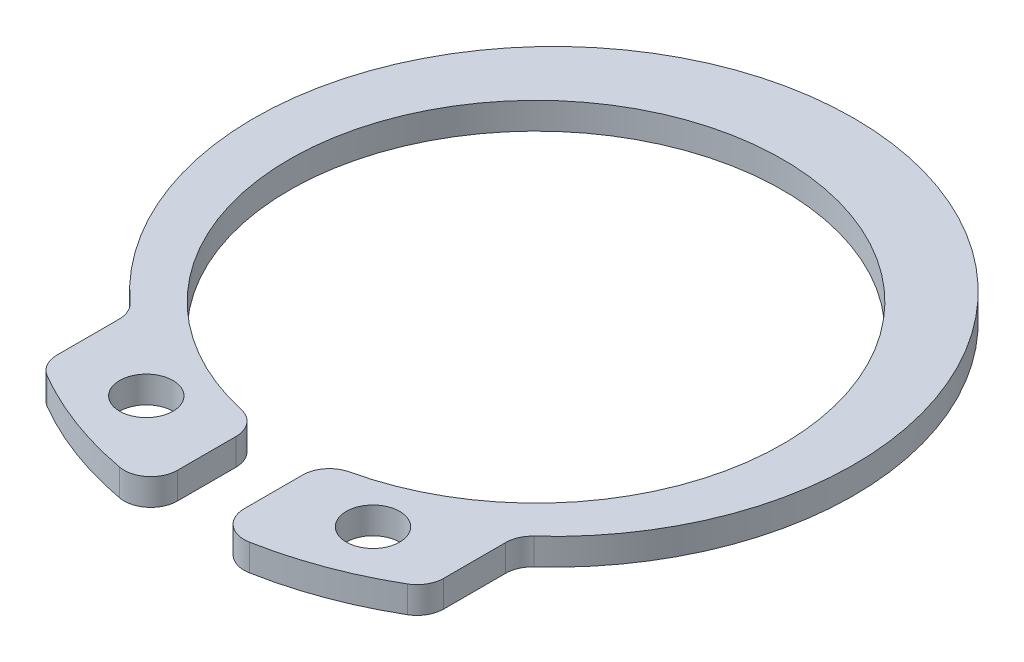
SolidWorks part; units mm, degrees
material "铸造合金钢"
ref_plane "Front" through (0, 0, 0) normal (0, 0, 1) x (1, 0, 0)
ref_plane "Top" through (0, 0, 0) normal (0, 1, 0) x (1, 0, 0)
ref_plane "Right" through (0, 0, 0) normal (1, 0, 0) x (0, 0, -1)
sketch "草图1" plane through (0, 0, 0) normal (0, 1, 0) x (1, 0, 0)
  line L0 (0, 6.1653) -> (0, -2.3077) construction
  line L1 (-1.25, -13.3416) -> (-1.25, -9.1652)
  line L2 (1.25, -13.3416) -> (1.25, -9.1652)
  line L3 (-4.25, -2.5592) -> (-4.25, -10.3623) construction
  line L4 (-7.25, -7.9323) -> (-7.25, -11.2693)
  line L5 (7.25, -7.9323) -> (7.25, -11.2693)
  line L6 (4.25, -2.5592) -> (4.25, -10.3623) construction
  line L7 (11.2, 0) -> (-11.2, 0) construction
  line L8 (0, 0) -> (-1.8108, -13.2771) construction
  arc A0 (1.25, -9.1652) -> (-1.25, -9.1652) centre (0, 0) ccw
  arc A1 (7.25, -7.9323) -> (-7.25, -7.9323) centre (0, 0.67) ccw
  arc A2 (-11.2, 0) -> (11.2, 0) centre (0, 0) ccw construction
  circle A3 centre (-4.25, -10.3623) radius 1
  arc A4 (-7.25, -11.2693) -> (-1.25, -13.3416) centre (0, 0) ccw
  circle A5 centre (4.25, -10.3623) radius 1
  arc A6 (7.25, -11.2693) -> (1.25, -13.3416) centre (0, 0) cw
  dimension "内径" = 18.5
  dimension "外径" = 22.5
  dimension "孔径" = 2
  dimension "孔心半径" = 11.2
  dimension "边圆半径" = 13.4
  dimension "偏心距离" = 0.67
  dimension "对边距离" = 14.5
  dimension "孔间距" = 8.5
  dimension "间隙距离" = 2.5
extrude "凸台-拉伸1" add sketch "草图1" along normal mid plane 1
fillet "圆角1" radius 1 8 edges at (1.25, 0, 9.1652) (7.25, 0, 11.2693) (1.25, 0, 13.3416) (-1.25, 0, 13.3416) (-1.25, 0, 9.1652) (-7.25, 0, 11.2693) (-7.25, 0, 7.9323) (7.25, 0, 7.9323)
other "冻结***"
